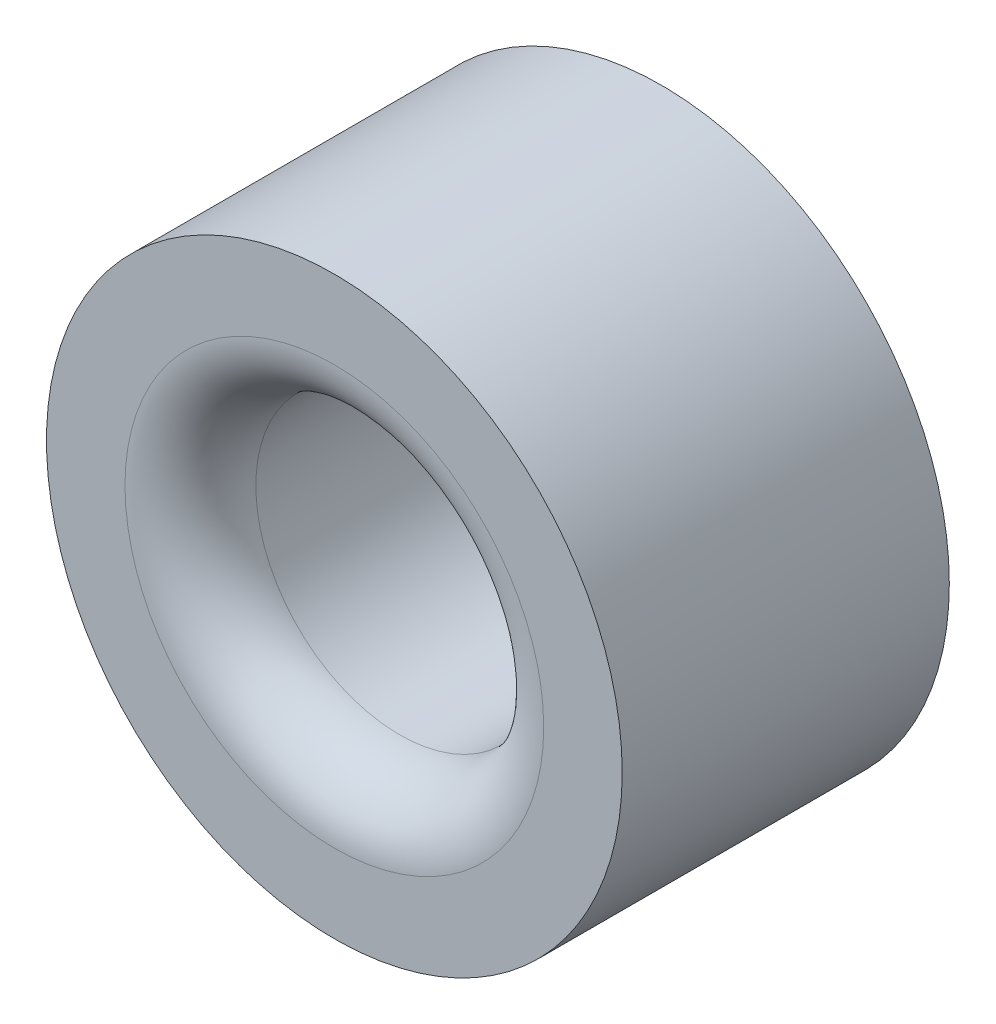
SolidWorks part; units mm, degrees
ref_plane "Front Plane" through (0, 0, 0) normal (0, 0, 1) x (1, 0, 0)
ref_plane "Top Plane" through (0, 0, 0) normal (0, 1, 0) x (1, 0, 0)
ref_plane "Right Plane" through (0, 0, 0) normal (1, 0, 0) x (0, 0, -1)
sketch "Sketch2" plane through (0, 0, 0) normal (0, 0, 1) x (1, 0, 0)
  circle A0 centre (0, 0) radius 1.397
  circle A1 centre (0, 0) radius 2.794
  dimension "D1" = 2.794
  dimension "D2" = 5.588
extrude "Boss-Extrude1" add sketch "Sketch2" along normal blind 3.175
fillet "Fillet1" radius 0.635 1 edges at (1.397, 0, 3.175)
